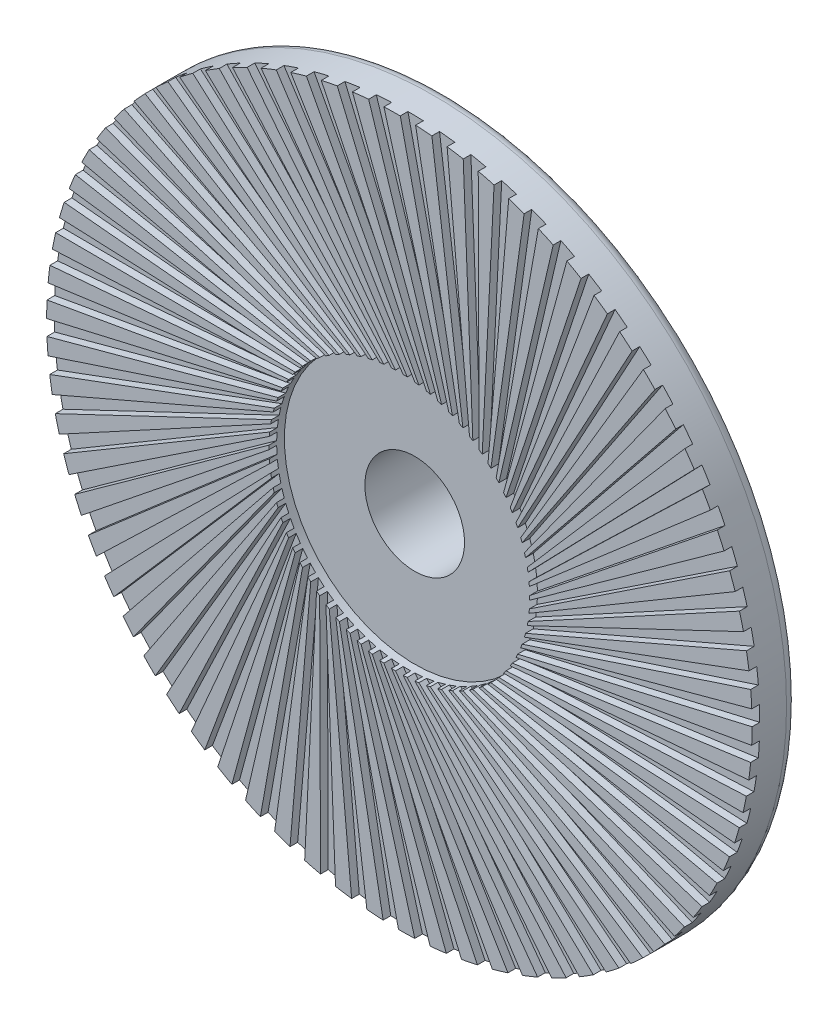
SolidWorks part; units mm, degrees
material "Aleación 1060"
ref_plane "Alzado" through (0, 0, 0) normal (0, 0, 1) x (1, 0, 0)
ref_plane "Planta" through (0, 0, 0) normal (0, 1, 0) x (1, 0, 0)
ref_plane "Vista lateral" through (0, 0, 0) normal (1, 0, 0) x (0, 0, -1)
sketch "Croquis1" plane through (0, 0, 0) normal (0, 0, 1) x (1, 0, 0)
  circle A0 centre (0, 0) radius 46
  dimension "D1" = 92
extrude "Saliente-Extruir1" add sketch "Croquis1" along normal blind 6
sketch "Croquis2" plane through (0, 0, 6) normal (0, 0, 1) x (1, 0, 0)
  line L3 (-0.5, 18.3618) -> (-0.5, 18.3593)
  line L257 (-18.0318, 42.3185) -> (0.5, 16.9926)
  line L258 (-0.5, 16.9926) -> (-19.8542, 41.4947)
  arc A0 (0.5, 16.9926) -> (-0.5, 16.9926) centre (0, 0) ccw
  circle A2 centre (0, 0) radius 46
  arc A3 (-18.0318, 42.3185) -> (-19.8542, 41.4947) centre (0, 0) ccw
  circle M2 centre (0, 0) radius 46
  dimension "D1" = 34
  dimension "D2" = 0
extrude "Cortar-Extruir1" cut sketch "Croquis2" against normal blind 1 contours A0 L257 L258 M2
pattern_circular "MatrizC1" count 70 over 360 about axis through (0, 0, 0) along (0, 0, 1) of "Cortar-Extruir1"
sketch "Croquis3" plane through (0, 0, 6) normal (0, 0, 1) x (1, 0, 0)
  circle A0 centre (0, 0) radius 17
  dimension "D1" = 34
extrude "Cortar-Extruir2" cut sketch "Croquis3" against normal blind 2
sketch "Croquis4" plane through (0, 0, 0) normal (0, 0, -1) x (-1, 0, 0)
  circle A2 centre (0, 0) radius 14
  dimension "D1" = 28
extrude "Saliente-Extruir2" add sketch "Croquis4" along normal blind 7
sketch "Croquis5" plane through (0, 0, -7) normal (0, 0, -1) x (-1, 0, 0)
  circle A0 centre (0, 0) radius 6.5
  dimension "D1" = 13
extrude "Cortar-Extruir3" cut sketch "Croquis5" against normal through all
fillet "Redondeo1" radius 2 1 edges at (-14, 0, -7)
sketch "Croquis6" plane through (0, 0, 0) normal (1, 0, 0) x (0, 0, -1)
  line L0 (0, 0) -> (7, 0) construction
  line L1 (-4, 0) -> (7, 0) construction
  line L2 (5, 0) -> (0, 0) construction
  line L3 (7, -12) -> (7, 12) construction
  circle A0 centre (7, 0) radius 1.5
  dimension "D1" = 3
extrude "Cortar-Extruir5" cut sketch "Croquis6" against normal mid plane 30
fillet "Redondeo2" radius 1.5 1 edges at (46, 0, 0)
fillet "Redondeo3" radius 1.5 1 edges at (14, 0, 0)
pattern_circular "MatrizC2" count 2 over 90 about axis through (0, 0, -1.5) along (0, 0, 1) of "Cortar-Extruir5"
